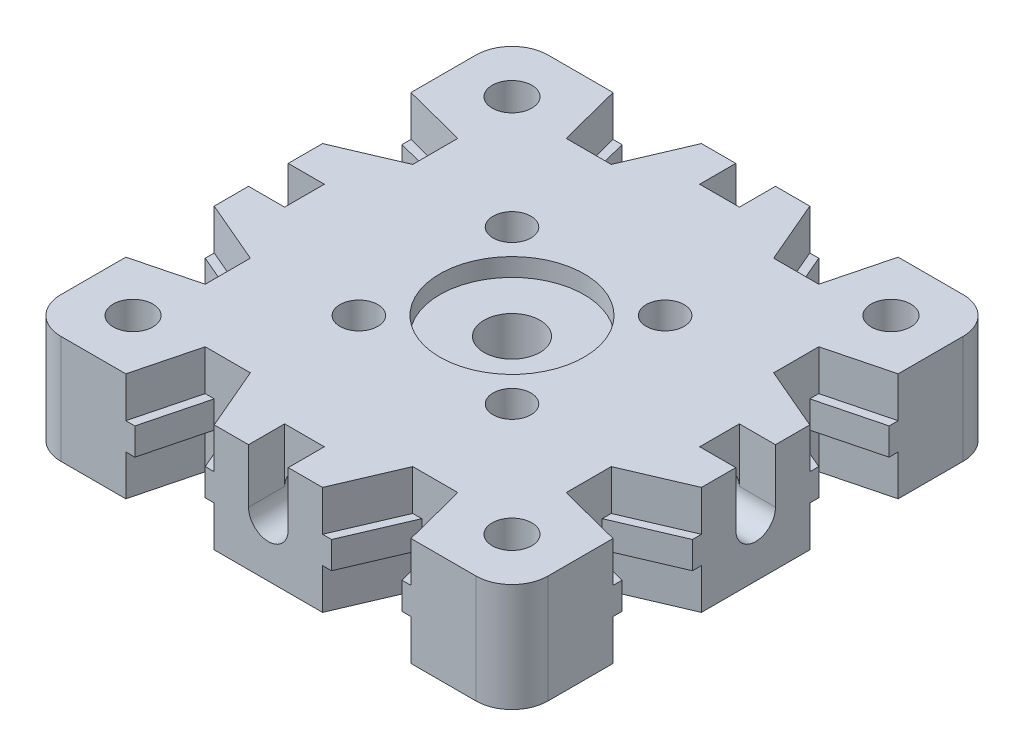
SolidWorks part; units mm, degrees
material "ABS"
ref_plane "正面" through (0, 0, 0) normal (0, 0, 1) x (1, 0, 0)
ref_plane "平面" through (0, 0, 0) normal (0, 1, 0) x (1, 0, 0)
ref_plane "右側面" through (0, 0, 0) normal (1, 0, 0) x (0, 0, -1)
sketch "ｽｹｯﾁ3" plane through (0, 0, 0) normal (0, 1, 0) x (1, 0, 0)
  line L1 (-13.5, 13.5) -> (13.5, 13.5)
  line L2 (-13.5, 13.5) -> (-13.5, -13.5)
  line L3 (-13.5, -13.5) -> (13.5, -13.5)
  line L4 (13.5, 13.5) -> (13.5, -13.5)
  line L5 (-13.5, 13.5) -> (13.5, -13.5) construction
  line L6 (-13.5, -13.5) -> (13.5, 13.5) construction
  point P0 (0, 0)
  dimension "D1" = 27
extrude "ﾎﾞｽ - 押し出し1" add sketch "ｽｹｯﾁ3" along normal mid plane 6
fillet "ﾌｨﾚｯﾄ1" radius 2 4 edges at (-13.5, 0, -13.5) (13.5, 0, -13.5) (-13.5, 0, 13.5) (13.5, 0, 13.5)
sketch "ｽｹｯﾁ4" plane through (0, 3, 0) normal (0, 1, 0) x (1, 0, 0)
  line L1 (-10.5, 10.5) -> (10.5, 10.5) construction
  line L2 (-10.5, 10.5) -> (-10.5, -10.5) construction
  line L3 (-10.5, -10.5) -> (10.5, -10.5) construction
  line L4 (10.5, 10.5) -> (10.5, -10.5) construction
  line L5 (-10.5, 10.5) -> (10.5, -10.5) construction
  line L6 (-10.5, -10.5) -> (10.5, 10.5) construction
  circle A0 centre (-10.5, 10.5) radius 1.1
  circle A1 centre (10.5, 10.5) radius 1.1
  circle A2 centre (-10.5, -10.5) radius 1.1
  circle A3 centre (10.5, -10.5) radius 1.1
  point P0 (0, 0)
  dimension "D6" = 2.2
  dimension "D1" = 21
  dimension "D2" = 21
extrude "ｶｯﾄ - 押し出し1" cut sketch "ｽｹｯﾁ4" against normal blind 6
sketch "ｽｹｯﾁ5" plane through (0, 3, 0) normal (0, 1, 0) x (1, 0, 0)
  circle A0 centre (0, 0) radius 1.55
  dimension "D1" = 3.1
extrude "ｶｯﾄ - 押し出し2" cut sketch "ｽｹｯﾁ5" against normal blind 6
sketch "ｽｹｯﾁ6" plane through (0, 3, 0) normal (0, 1, 0) x (1, 0, 0)
  line L0 (4.2426, 4.2426) -> (0, 0)
  line L1 (0, 0) -> (3.3762, 0)
  circle A0 centre (4.2426, 4.2426) radius 1.05
  dimension "D1" = 2.1
  dimension "D2" = 45
  dimension "D3" = 6
extrude "ｶｯﾄ - 押し出し3" cut sketch "ｽｹｯﾁ6" against normal blind 6
pattern_circular "円形ﾊﾟﾀｰﾝ1" count 4 over 360 about axis through (0, 0, 0) along (0, 1, 0) of "ｶｯﾄ - 押し出し3"
sketch "ｽｹｯﾁ7" plane through (0, 3, 0) normal (0, 1, 0) x (1, 0, 0)
  circle A0 centre (0, 0) radius 4
  dimension "D1" = 8
extrude "ｶｯﾄ - 押し出し4" cut sketch "ｽｹｯﾁ7" against normal blind 1
sketch "ｽｹｯﾁ8" plane through (0, -3, 0) normal (0, -1, 0) x (1, 0, 0)
  line L1 (-5.6, -5.6) -> (5.6, -5.6)
  line L2 (-5.6, -5.6) -> (-5.6, 5.6)
  line L3 (-5.6, 5.6) -> (5.6, 5.6)
  line L4 (5.6, -5.6) -> (5.6, 5.6)
  line L5 (-5.6, -5.6) -> (5.6, 5.6) construction
  line L6 (-5.6, 5.6) -> (5.6, -5.6) construction
  point P0 (0, 0)
  dimension "D1" = 11.2
extrude "ｶｯﾄ - 押し出し5" cut sketch "ｽｹｯﾁ8" against normal blind 2.5
sketch "ｽｹｯﾁ10" plane through (0, -3, 0) normal (0, -1, 0) x (1, 0, 0)
  circle A0 centre (4.2426, 4.2426) radius 2.35
  circle A1 centre (-4.2426, 4.2426) radius 2.35
  circle A2 centre (4.2426, -4.2426) radius 2.35
  circle A3 centre (-4.2426, -4.2426) radius 2.35
  dimension "D2" = 4.7
extrude "ｶｯﾄ - 押し出し7" [suppressed] cut sketch "ｽｹｯﾁ10" against normal blind 4
sketch "ｽｹｯﾁ11" plane through (0, 3, 0) normal (0, 1, 0) x (1, 0, 0)
  line L0 (3, 13.5) -> (4.5, 10)
  line L1 (11.5, 13.5) -> (-11.5, 13.5) construction
  line L2 (4.5, 10) -> (7, 10)
  line L3 (7, 10) -> (7.9, 13.5)
  dimension "D1" = 3.5
  dimension "D2" = 2.5
  dimension "D3" = 7
  dimension "D4" = 3
  dimension "D5" = 7.9
extrude "ｶｯﾄ - 押し出し8" cut sketch "ｽｹｯﾁ11" against normal through all and the other way through all
mirror "ﾐﾗｰ1" about plane through (0, 0, 0) normal (1, 0, 0) of "ｶｯﾄ - 押し出し8"
pattern_circular "円形ﾊﾟﾀｰﾝ2" count 4 over 360 about axis through (0, 0, 0) along (0, 1, 0) of "ｶｯﾄ - 押し出し8", "ﾐﾗｰ1"
sketch "ｽｹｯﾁ12" plane through (0, 0, 13.5) normal (0, 0, 1) x (1, 0, 0)
  circle A0 centre (0, 0) radius 1.1
  dimension "D1" = 2.2
extrude "ｶｯﾄ - 押し出し9" cut sketch "ｽｹｯﾁ12" against normal blind 8
pattern_circular "円形ﾊﾟﾀｰﾝ3" count 4 over 360 about axis through (0, 0, 0) along (0, 1, 0) of "ｶｯﾄ - 押し出し9"
sketch "ｽｹｯﾁ13" plane through (0, 0, 0) normal (0, 1, 0) x (1, 0, 0)
  line L0 (7.9, 13.5) -> (7, 10)
  line L1 (7, 10) -> (6.5, 10)
  line L2 (7, 10) -> (4.5, 10) construction
  line L3 (6.5, 10) -> (7.4, 13.5)
  line L4 (7.4, 13.5) -> (7.9, 13.5)
  line L5 (3, 13.5) -> (3.5, 13.5)
  line L6 (3.5, 13.5) -> (5, 10)
  line L7 (5, 10) -> (4.5, 10)
  line L8 (4.5, 10) -> (3, 13.5)
  dimension "D1" = 0.5
  dimension "D2" = 0.5
extrude "ﾎﾞｽ - 押し出し2" add sketch "ｽｹｯﾁ13" along normal mid plane 1.5
mirror "ﾐﾗｰ2" about plane through (0, 0, 0) normal (1, 0, 0) of "ﾎﾞｽ - 押し出し2"
pattern_circular "円形ﾊﾟﾀｰﾝ4" count 4 over 360 about axis through (0, 0, 0) along (0, 1, 0) of "ﾎﾞｽ - 押し出し2", "ﾐﾗｰ2"
ref_plane "平面1" through (0, 0, -10.5) normal (0, 0, -1) x (-1, 0, 0)
sketch "ｽｹｯﾁ22" plane through (0, 0, 13.5) normal (0, 0, 1) x (1, 0, 0)
  line L0 (0, 3) -> (6, 3) construction
  line L1 (-1.1, 0) -> (1.1, 0)
  line L2 (-1.1, 0) -> (-1.1, 3)
  line L3 (-1.1, 3) -> (1.1, 3)
  line L4 (1.1, 0) -> (1.1, 3)
  line L5 (-1.1, 0) -> (1.1, 3) construction
  line L6 (-1.1, 3) -> (1.1, 0) construction
  arc A0 (0.9798, -0.5) -> (-0.9798, -0.5) centre (0, 0) ccw construction
  circle A1 centre (0, 0) radius 1.1 construction
  point P4 (0, 1.5)
extrude "ｶｯﾄ - 押し出し15" cut sketch "ｽｹｯﾁ22" against normal blind 2
sketch "ｽｹｯﾁ23" plane through (0, -3, 0) normal (0, -1, 0) x (1, 0, 0)
  line L1 (-8, 8) -> (-4.4, 8)
  line L2 (-8, 8) -> (-8, 4.4)
  line L3 (-8, 4.4) -> (-4.4, 4.4)
  line L4 (-4.4, 8) -> (-4.4, 4.4)
  line L5 (-8, 8) -> (-4.4, 4.4) construction
  line L6 (-8, 4.4) -> (-4.4, 8) construction
  circle A0 centre (-4.2426, 4.2426) radius 2.9
  point P8 (-6.2, 6.2)
  dimension "D1" = 5.8
  dimension "D2" = 8
  dimension "D3" = 8
  dimension "D4" = 4.4
extrude "ｶｯﾄ - 押し出し16" cut sketch "ｽｹｯﾁ23" against normal blind 3.5 contours A0 L4 L1 L2 L3
pattern_circular "円形ﾊﾟﾀｰﾝ8" count 4 over 360 about axis through (0, 0, 0) along (0, 1, 0) of "ｶｯﾄ - 押し出し16"
fillet "ﾌｨﾚｯﾄ2" radius 0.3 20 edges at (-4.4, -1.25, -7.1384) (-4.4, -1.25, -8) (-8, -1.25, -8) (-7.1384, -1.25, -4.4) (-8, -1.25, -4.4) (8, -1.25, -8) (4.4, -1.25, -8) (4.4, -1.25, -7.1384) (8, -1.25, -4.4) (7.1384, -1.25, -4.4) (7.1384, -1.25, 4.4) (8, -1.25, 4.4) (8, -1.25, 8) (4.4, -1.25, 7.1384) (4.4, -1.25, 8) (-4.4, -1.25, 7.1384) (-7.1384, -1.25, 4.4) (-8, -1.25, 4.4) (-8, -1.25, 8) (-4.4, -1.25, 8)
sketch "ｽｹｯﾁ25" plane through (0, -3, 0) normal (0, -1, 0) x (1, 0, 0)
  line L3 (-7.4098, 4.4) -> (-4.4, 4.4)
  line L4 (-4.4, 4.4) -> (-4.4, 7.4098)
  line L5 (-4.4, 7.4098) -> (-7.4098, 7.4098)
  line L6 (-7.4098, 7.4098) -> (-7.4098, 4.4)
extrude "ｶｯﾄ - 押し出し17" cut sketch "ｽｹｯﾁ25" against normal up to surface (2.5 mm away) up to face at (4.2426, -0.5, -3.1926)
pattern_circular "円形ﾊﾟﾀｰﾝ10" count 4 over 360 about axis through (0, 0, 0) along (0, 1, 0) of "ｶｯﾄ - 押し出し17"
pattern_circular "円形ﾊﾟﾀｰﾝ11" count 4 over 360 about axis through (0, 0, 0) along (0, 1, 0) of "ｶｯﾄ - 押し出し15"
